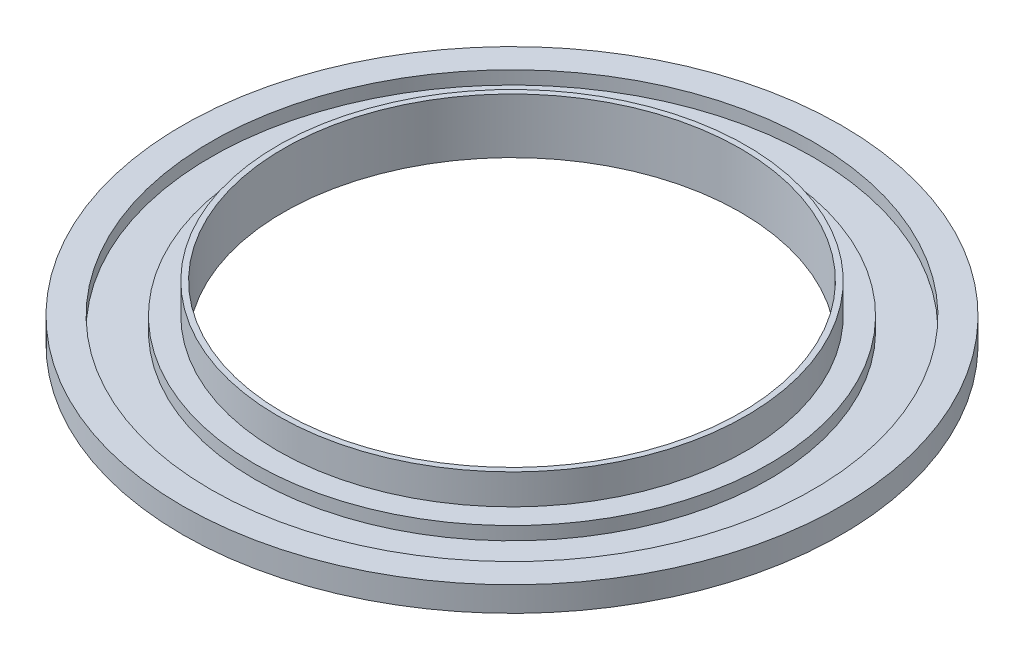
SolidWorks part; units mm, degrees
ref_plane "Front Plane" through (0, 0, 0) normal (0, 0, 1) x (1, 0, 0)
ref_plane "Top Plane" through (0, 0, 0) normal (0, 1, 0) x (1, 0, 0)
ref_plane "Right Plane" through (0, 0, 0) normal (1, 0, 0) x (0, 0, -1)
sketch "Sketch3" plane through (0, 0, 0) normal (1, 0, 0) x (0, 0, -1)
  line L0 (-212.5, 8.0703) -> (-212.5, 35.5532)
  line L1 (-299, 8.0703) -> (-273.25, 8.0703)
  line L2 (-299, 8.0703) -> (-299, -14.4468)
  line L3 (-299, -14.4468) -> (-207.5, -14.4468)
  line L5 (-273.25, 8.0703) -> (-273.25, -3.9297)
  line L6 (-273.25, -3.9297) -> (-233.25, -3.9297)
  line L7 (-212.5, 35.5532) -> (-207.5, 35.5532)
  line L9 (-233.25, -3.9297) -> (-233.25, 8.0703)
  line L10 (-233.25, 8.0703) -> (-212.5, 8.0703)
  line L11 (-253.25, 0) -> (-253.25, -22.5537) construction
  line L12 (0, 120.738) -> (0, -95.9334) construction
  line L13 (-207.5, 35.5532) -> (-207.5, 8.0703)
  line L14 (-207.5, -14.4468) -> (-207.5, 8.0703)
  point P7 (-210, 35.5532)
  point P14 (-253.25, -14.4468)
  point P16 (-253.25, -3.9297)
  dimension "D2" = 50
  dimension "D3" = 91.5
  dimension "D4" = 5
  dimension "D6" = 12
  dimension "D7" = 40
  dimension "D8" = 12
revolve "Revolve1" add sketch "Sketch3" angle 360 about L12
